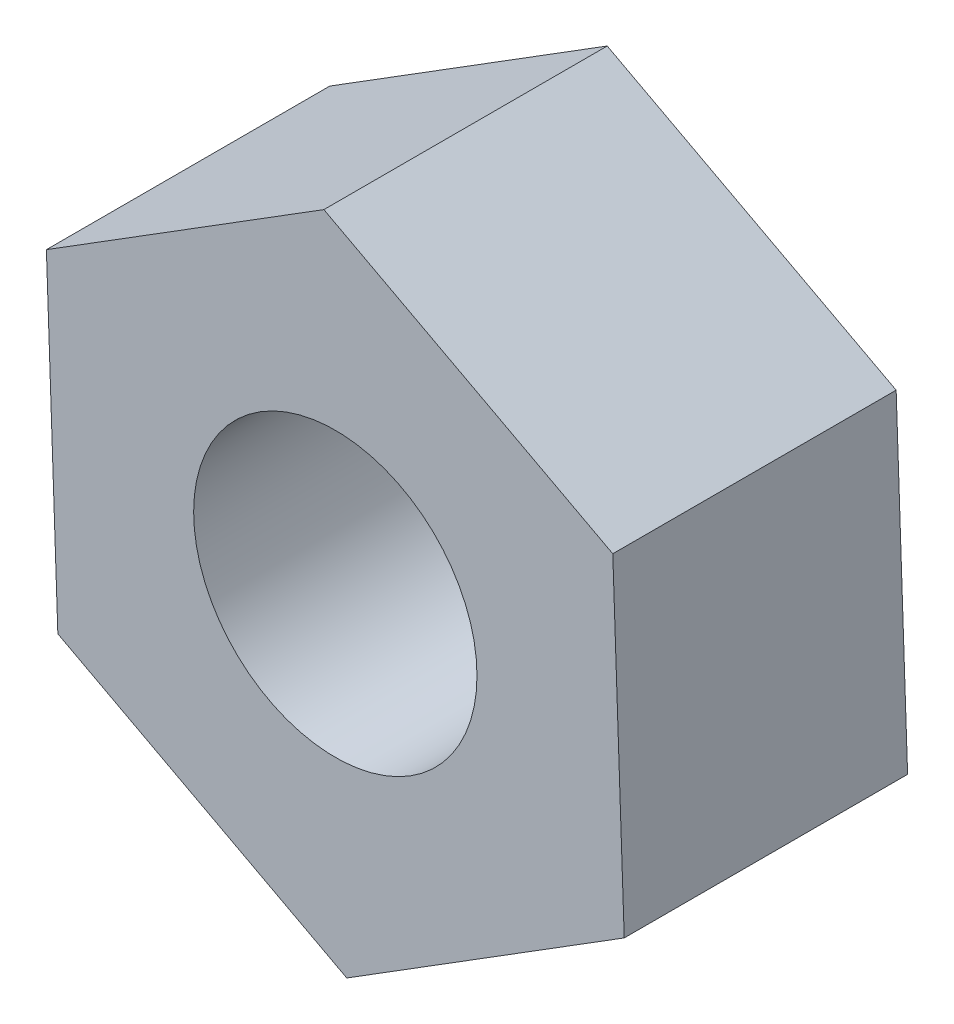
SolidWorks part; units mm, degrees
ref_plane "正面" through (0, 0, 0) normal (0, 0, 1) x (1, 0, 0)
ref_plane "平面" through (0, 0, 0) normal (0, 1, 0) x (1, 0, 0)
ref_plane "右側面" through (0, 0, 0) normal (1, 0, 0) x (0, 0, -1)
sketch "ｽｹｯﾁ1" plane through (0, 0, 0) normal (0, 0, 1) x (1, 0, 0)
  line L1 (3.9167, 2.448) -> (-0.1616, 4.616)
  line L2 (-0.1616, 4.616) -> (-4.0784, 2.168)
  line L3 (-4.0784, 2.168) -> (-3.9167, -2.448)
  line L4 (-3.9167, -2.448) -> (0.1616, -4.616)
  line L5 (0.1616, -4.616) -> (4.0784, -2.168)
  line L6 (4.0784, -2.168) -> (3.9167, 2.448)
  circle A0 centre (0, 0) radius 4 construction
  circle A1 centre (0, 0) radius 2
  dimension "D2" = 4
  dimension "D1" = 8
extrude "ﾎﾞｽ - 押し出し1" add sketch "ｽｹｯﾁ1" along normal blind 4
cosmetic thread "ねじ山1" parameters "D2"=12
